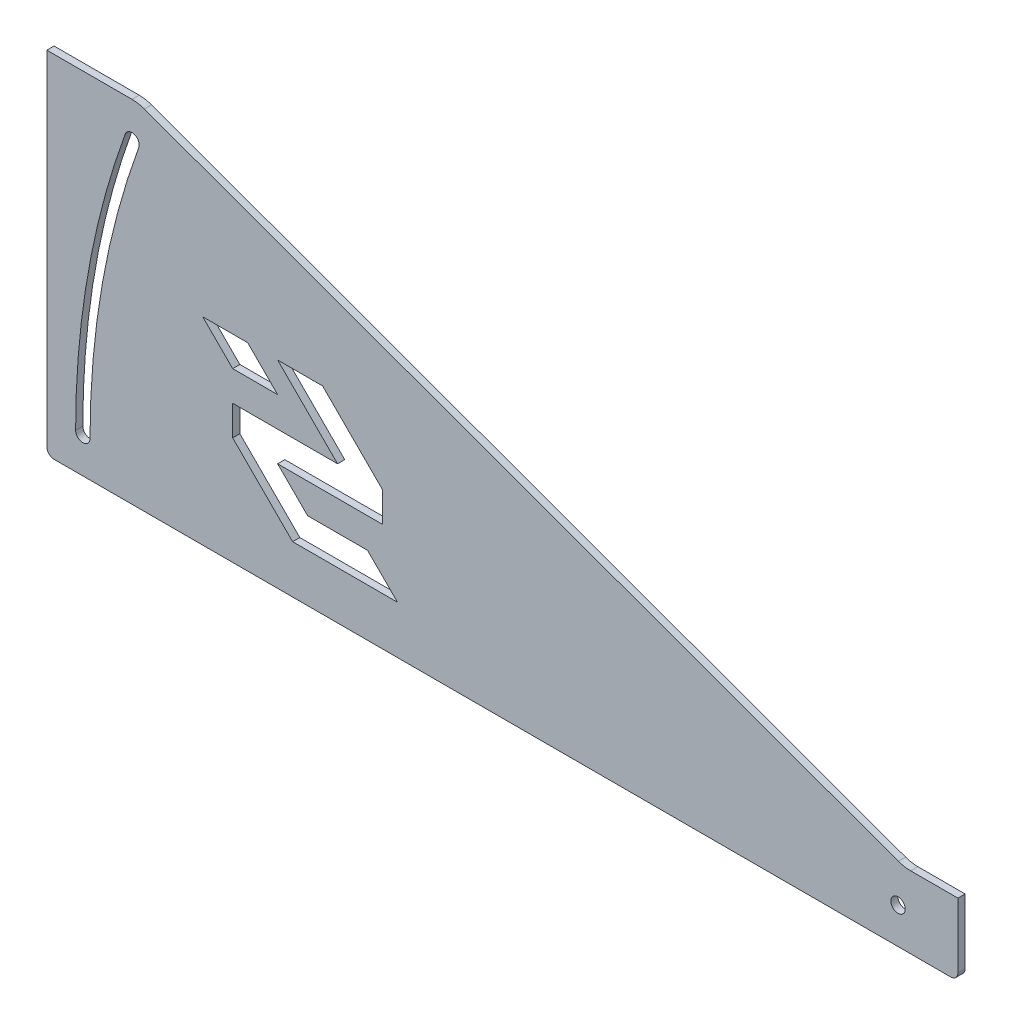
SolidWorks part; units mm, degrees
ref_plane "Front Plane" through (0, 0, 0) normal (0, 0, 1) x (1, 0, 0)
ref_plane "Top Plane" through (0, 0, 0) normal (0, 1, 0) x (1, 0, 0)
ref_plane "Right Plane" through (0, 0, 0) normal (1, 0, 0) x (0, 0, -1)
sketch "Sketch1" plane through (0, 0, 0) normal (0, 0, 1) x (1, 0, 0)
  line L0 (-185, -58.1434) -> (185, -58.1434) construction
  line L1 (-185, 73.1434) -> (185, 73.1434)
  line L2 (-185, 73.1434) -> (-185, -73.1434)
  line L3 (-185, -73.1434) -> (185, -73.1434)
  line L4 (185, 73.1434) -> (185, -73.1434)
  line L5 (-185, 73.1434) -> (185, -73.1434) construction
  line L6 (-185, -73.1434) -> (185, 73.1434) construction
  line L7 (170, -58.1434) -> (-170, -58.1434) construction
  line L9 (-149.4955, 58.1434) -> (170, -58.1434) construction
  line L10 (-149.4955, 58.1434) -> (-149.4955, 73.1434) construction
  line L11 (-170, -58.1434) -> (-170, -73.1434) construction
  line L12 (175.1303, -44.048) -> (-146.8506, 73.1434)
  line L13 (-170, -65.6434) -> (-185, -65.6434) construction
  line L21 (170, -43.1434) -> (195, -43.1434)
  line L22 (170, -43.1434) -> (170, -73.1434)
  line L23 (170, -73.1434) -> (195, -73.1434)
  line L24 (195, -43.1434) -> (195, -73.1434)
  circle A0 centre (170, -58.1434) radius 15
  circle A1 centre (170, -58.1434) radius 3
  circle A2 centre (170, -58.1434) radius 340
  circle A3 centre (-170, -58.1434) radius 3
  circle A13 centre (-149.4955, 58.1434) radius 3
  circle A14 centre (-169.7929, -46.2776) radius 3 [skipped]
  circle A15 centre (-169.1718, -34.4262) radius 3 [skipped]
  circle A16 centre (-168.1374, -22.6037) radius 3 [skipped]
  circle A17 centre (-166.6911, -10.8246) radius 3 [skipped]
  circle A18 centre (-164.8346, 0.897) radius 3 [skipped]
  circle A19 centre (-162.5702, 12.5466) radius 3 [skipped]
  circle A20 centre (-159.9005, 24.11) radius 3 [skipped]
  circle A21 centre (-156.829, 35.5733) radius 3 [skipped]
  circle A22 centre (-153.3592, 46.9224) radius 3 [skipped]
  circle A23 centre (170, -58.1434) radius 343
  circle A24 centre (170, -58.1434) radius 337
  point P0 (0, 0)
  dimension "D3" = 30
  dimension "D4" = 6
  dimension "D5" = 680
  dimension "D1" = 380
  dimension "D2" = 20
  dimension "D6" = 11
extrude "Boss-Extrude1" add sketch "Sketch1" along normal blind 3 contours L12 A24 L3 A0 L21 | A1 L22 A0 | A1 L22 A0 | A0 L3 L4 | L24 L21 L4 L23 | A0 L4 L21 L12 | A24 L12 A2 A13 | L1 A23 A13 A2 L12 | A23 L1 L2 L3 | A3 A23 L3 A2 | A24 A3 A2 L3 | A0 L12 L21
fillet "Fillet1" radius 15 2 edges at (-146.8506, 73.1434, 1.5) (172.6449, -43.1434, 1.5)
fillet "Fillet2" radius 3 2 edges at (195, -73.1434, 1.5) (-185, -73.1434, 1.5)
sketch "Sketch4" [suppressed] plane through (0, 0, 3) normal (0, 0, 1) x (1, 0, 0)
  line L2 (-182, -73.1434) -> (192, -73.1434) construction
  line L3 (-185, 73.1434) -> (-185, -70.1434) construction
  line L19 (-145, -53.1434) -> (-70, -53.1434)
  line L20 (-145, -53.1434) -> (-82.5, 9.3566)
  line L21 (-70, -53.1434) -> (-7.5, 9.3566)
  line L22 (-82.5, 9.3566) -> (-7.5, 9.3566)
  line L23 (-126.25, -53.1434) -> (-63.75, 9.3566)
  line L24 (-107.5, -53.1434) -> (-45, 9.3566)
  line L25 (-88.75, -53.1434) -> (-26.25, 9.3566)
  line L26 (-132.5, -40.6434) -> (-57.5, -40.6434)
  line L27 (-120, -28.1434) -> (-45, -28.1434)
  line L28 (-107.5, -15.6434) -> (-32.5, -15.6434)
  line L29 (-95, -3.1434) -> (-20, -3.1434)
  line L30 (-57.5, -40.6434) -> (-45, -40.6434) construction
  line L31 (-45, -28.1434) -> (-32.5, -28.1434) construction
  line L32 (-45, -28.1434) -> (-45, -40.6434) construction
  line L33 (-20, -15.6434) -> (-20, -3.1434) construction
  line L34 (-32.5, -15.6434) -> (-32.5, -28.1434) construction
  line L35 (-32.5, -15.6434) -> (-20, -15.6434) construction
  line L36 (-57.5, -40.6434) -> (-57.5, -53.1434) construction
  line L37 (-57.5, -53.1434) -> (-70, -53.1434) construction
  line L38 (-45, -28.1434) -> (-45, -15.6434)
  line L39 (-45, -15.6434) -> (-45, -3.1434) construction
  line L40 (-45, -3.1434) -> (-32.5, 9.3566)
  line L41 (-63.75, -3.1434) -> (-51.25, 9.3566)
  line L42 (-57.5, 3.1066) -> (-38.75, 3.1066) construction
  line L43 (-70, 3.1066) -> (-88.75, 3.1066) construction
  line L44 (-107.5, -15.6434) -> (-107.5, -28.1434)
  line L45 (-101.25, -40.6434) -> (-113.75, -53.1434)
  dimension "D1" = 20
  dimension "D2" = 40
  dimension "D4" = 45
  dimension "D5" = 75
  dimension "D6" = 62.5
  dimension "D8" = 18.75
  dimension "D9" = 12.5
  dimension "D7" = 4
extrude "Cut-Extrude1" [suppressed] cut sketch "Sketch4" against normal up to next contours L29 L40 L22 L24 | L41 L29 L24 L22 | L20 L29 L23 L22 | L29 L20 L28 L23 | L28 L44 L27 L23 | L28 L23 L27 L24 | L28 L24 L27 L25 | L27 L38 L28 L25 | L27 L25 L26 L21 | L26 L25 L19 L21 | L26 L24 L19 L25 | L26 L45 L19 L24
sketch "Sketch5" plane through (0, 0, 0) normal (0, 0, -1) x (-1, 0, 0)
  line L4 (185, 73.1434) -> (185, -70.1434) construction
  line L5 (182, -73.1434) -> (-192, -73.1434) construction
  line L19 (7.5, -53.1434) -> (82.5, -53.1434)
  line L20 (7.5, -53.1434) -> (70, 9.3566)
  line L21 (82.5, -53.1434) -> (145, 9.3566)
  line L22 (70, 9.3566) -> (145, 9.3566)
  line L23 (26.25, -53.1434) -> (88.75, 9.3566)
  line L24 (45, -53.1434) -> (107.5, 9.3566)
  line L25 (63.75, -53.1434) -> (126.25, 9.3566)
  line L26 (20, -40.6434) -> (95, -40.6434)
  line L27 (32.5, -28.1434) -> (107.5, -28.1434)
  line L28 (45, -15.6434) -> (120, -15.6434)
  line L29 (57.5, -3.1434) -> (132.5, -3.1434)
  line L30 (95, -40.6434) -> (107.5, -40.6434) construction
  line L31 (107.5, -28.1434) -> (120, -28.1434) construction
  line L32 (107.5, -28.1434) -> (107.5, -40.6434) construction
  line L33 (132.5, -15.6434) -> (132.5, -3.1434) construction
  line L34 (120, -15.6434) -> (120, -28.1434) construction
  line L35 (120, -15.6434) -> (132.5, -15.6434) construction
  line L36 (95, -40.6434) -> (95, -53.1434) construction
  line L37 (95, -53.1434) -> (82.5, -53.1434) construction
  line L38 (107.5, -28.1434) -> (107.5, -15.6434)
  line L39 (107.5, -15.6434) -> (107.5, -3.1434) construction
  line L40 (107.5, -3.1434) -> (120, 9.3566)
  line L41 (88.75, -3.1434) -> (101.25, 9.3566)
  line L42 (95, 3.1066) -> (113.75, 3.1066) construction
  line L43 (82.5, 3.1066) -> (63.75, 3.1066) construction
  line L44 (45, -15.6434) -> (45, -28.1434)
  line L45 (51.25, -40.6434) -> (38.75, -53.1434)
  point P0 (87.7985, -55.5745)
  dimension "D1" = 40
  dimension "D2" = 20
  dimension "D4" = 45
  dimension "D5" = 75
  dimension "D6" = 62.5
  dimension "D8" = 18.75
  dimension "D9" = 12.5
  dimension "D7" = 4
extrude "Cut-Extrude2" cut sketch "Sketch5" against normal up to next contours L29 L40 L22 L24 | L41 L29 L24 L22 | L20 L29 L23 L22 | L29 L20 L28 L23 | L28 L44 L27 L23 | L28 L23 L27 L24 | L28 L24 L27 L25 | L27 L38 L28 L25 | L27 L25 L26 L21 | L26 L25 L19 L21 | L26 L24 L19 L25 | L26 L45 L19 L24
equation "\"D5@Sketch1\"=340*2"
